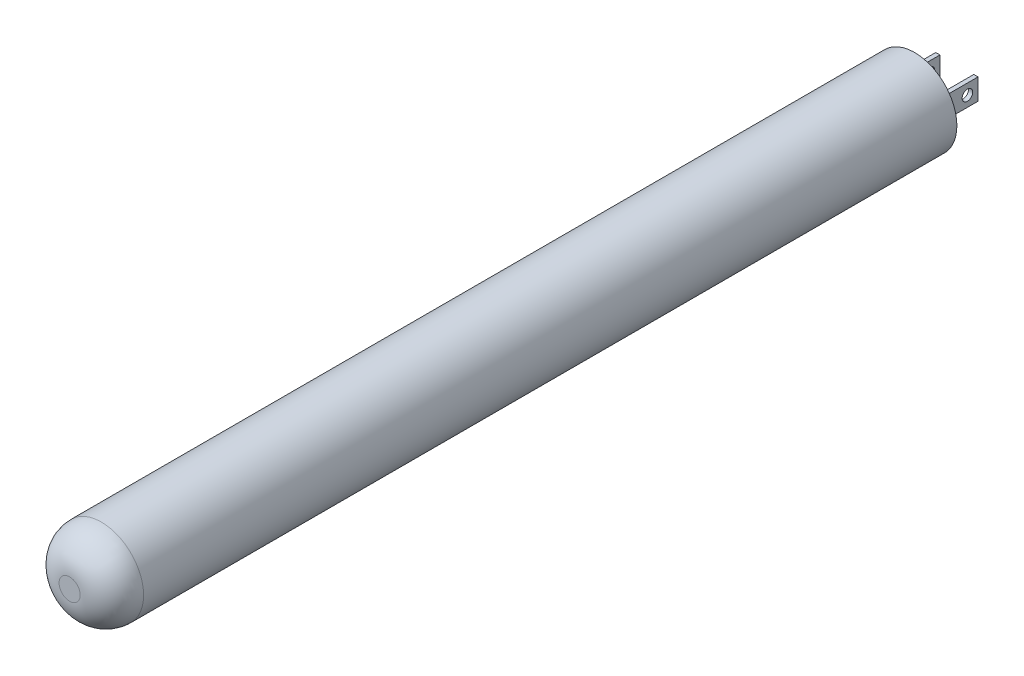
SolidWorks part; units mm, degrees
ref_plane "Front Plane" through (0, 0, 0) normal (0, 0, 1) x (1, 0, 0)
ref_plane "Top Plane" through (0, 0, 0) normal (0, 1, 0) x (1, 0, 0)
ref_plane "Right Plane" through (0, 0, 0) normal (1, 0, 0) x (0, 0, -1)
sketch "Sketch1" plane through (0, 0, 0) normal (0, 0, 1) x (1, 0, 0)
  circle A0 centre (0, 0) radius 20
extrude "Boss-Extrude1" add sketch "Sketch1" along normal mid plane 400
fillet "Fillet2" radius 15 1 edges at (20, 0, 200)
sketch "Sketch2" plane through (0, 0, 0) normal (0, 0, 1) x (1, 0, 0)
  line L0 (0, 0) -> (0, 3.3965)
  line L1 (10, -5) -> (8, -5)
  line L2 (10, -5) -> (10, 5)
  line L3 (10, 5) -> (8, 5)
  line L4 (8, -5) -> (8, 5)
  line L5 (10, -5) -> (8, 5) construction
  line L6 (10, 5) -> (8, -5) construction
  line L7 (-10, -5) -> (-8, -5)
  line L8 (-10, -5) -> (-10, 5)
  line L9 (-10, 5) -> (-8, 5)
  line L10 (-8, -5) -> (-8, 5)
  point P0 (9, 0)
  dimension "D1" = 10
  dimension "D2" = 2
extrude "Boss-Extrude2" add sketch "Sketch2" against normal blind 20 from surface at -200 contours L7 L10 L9 L8 | L4 L1 L2 L3 starting at face at (20, 0, -200)
sketch "Sketch3" plane through (0, 0, 0) normal (1, 0, 0) x (0, 0, -1)
  circle A0 centre (215, 0) radius 2.5
extrude "Cut-Extrude1" cut sketch "Sketch3" against normal mid plane 22
